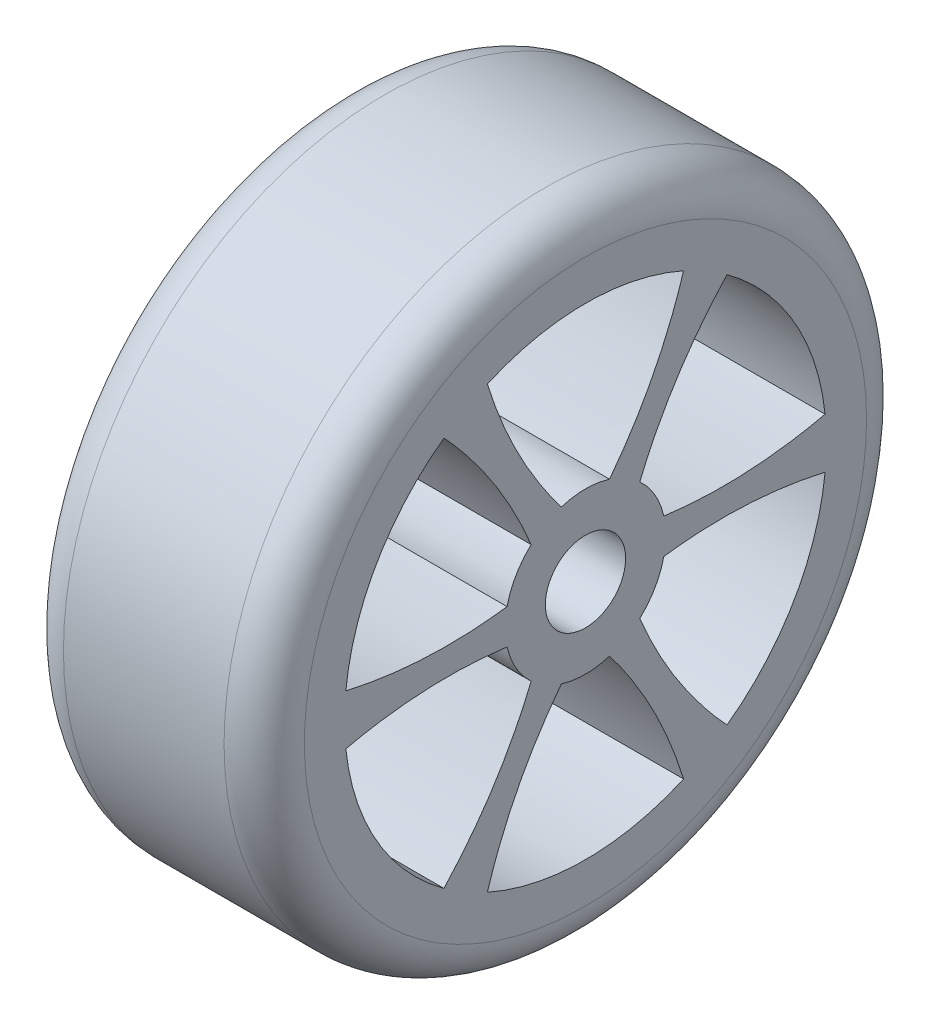
SolidWorks part; units mm, degrees
ref_plane "Front Plane" through (0, 0, 0) normal (1, 0, 0) x (0, 1, 0)
ref_plane "Top Plane" through (0, 0, 0) normal (0, 0, 1) x (0, 1, 0)
ref_plane "Right Plane" through (0, 0, 0) normal (0, 1, 0) x (-1, 0, 0)
sketch "Sketch1" plane through (0, 0, 0) normal (1, 0, 0) x (0, 1, 0)
  line L0 (0, 0) -> (0, 125.8279) construction
  circle A0 centre (0, 0) radius 101.6
  circle A1 centre (0, 0) radius 76.2
  circle A2 centre (0, 0) radius 25.4
  circle A3 centre (0, 0) radius 76.2
  circle A4 centre (0, 0) radius 76.2
  circle A5 centre (0, 0) radius 76.2
  spline S0 degree 2 poles (-22.4008, 72.833) (-10.4924, 49.373) (-10.8441, 22.9688) knots 0 0 0 1 1 1
  spline S1 degree 2 poles (22.4008, 72.833) (10.4924, 49.373) (10.8441, 22.9688) knots 0 0 0 1 1 1
  spline S2 degree 2 poles (72.833, 22.4008) (49.373, 10.4924) (22.9688, 10.8441) knots 0 0 0 1 1 1
  spline S3 degree 2 poles (72.833, -22.4008) (49.373, -10.4924) (22.9688, -10.8441) knots 0 0 0 1 1 1
  spline S4 degree 2 poles (22.4008, -72.833) (10.4924, -49.373) (10.8441, -22.9688) knots 0 0 0 1 1 1
  spline S5 degree 2 poles (-22.4008, -72.833) (-10.4924, -49.373) (-10.8441, -22.9688) knots 0 0 0 1 1 1
  spline S6 degree 2 poles (-72.833, -22.4008) (-49.373, -10.4924) (-22.9688, -10.8441) knots 0 0 0 1 1 1
  spline S7 degree 2 poles (-72.833, 22.4008) (-49.373, 10.4924) (-22.9688, 10.8441) knots 0 0 0 1 1 1
  point P36 (0, 0)
  dimension "D1" = 203.2
  dimension "D2" = 152.4
  dimension "D3" = 50.8
  dimension "D4" = 4
extrude "Boss-Extrude1" add sketch "Sketch1" along normal blind 76.2 contours A0
fillet "Fillet1" radius 12.7 2 edges at (0, 0, -101.6) (76.2, 0, -101.6)
sketch "Sketch2" plane through (76.2, 0, 0) normal (1, 0, 0) x (0, 1, 0)
  line L0 (0, 0) -> (0, 25.4) construction
  line L1 (0, 76.2) -> (0, 107.8241) construction
  arc A0 (-24.2324, 7.6125) -> (-24.2324, -7.6125) centre (0, 0) ccw
  arc A1 (-69.5977, 31.0259) -> (-69.5977, -31.0259) centre (0, 0) ccw
  arc A2 (18.7088, 17.1797) -> (5.5236, 24.7921) centre (0, 0) ccw
  arc A3 (61.668, 44.7604) -> (7.9296, 75.7863) centre (0, 0) ccw
  arc A4 (24.2324, -7.6125) -> (24.2324, 7.6125) centre (0, 0) ccw
  arc A5 (69.5977, -31.0259) -> (69.5977, 31.0259) centre (0, 0) ccw
  arc A6 (-61.668, -44.7604) -> (-7.9296, -75.7863) centre (0, 0) ccw
  arc A7 (-18.7088, -17.1797) -> (-5.5236, -24.7921) centre (0, 0) ccw
  arc A8 (5.5236, -24.7921) -> (18.7088, -17.1797) centre (0, 0) ccw
  arc A9 (7.9296, -75.7863) -> (61.668, -44.7604) centre (0, 0) ccw
  arc A10 (-7.9296, 75.7863) -> (-61.668, 44.7604) centre (0, 0) ccw
  arc A11 (-5.5236, 24.7921) -> (-18.7088, 17.1797) centre (0, 0) ccw
  spline S0 degree 2 poles (-5.5236, 24.7921) (-2.1408, 50.4497) (-7.9296, 75.7863) knots 0 0 0 1 1 1
  spline S1 degree 2 poles (5.5236, 24.7921) (2.1408, 50.4497) (7.9296, 75.7863) knots 0 0 0 1 1 1
  spline S2 degree 2 poles (18.7088, 17.1797) (42.6203, 27.0789) (61.668, 44.7604) knots 0 0 0 1 1 1
  spline S3 degree 2 poles (24.2324, 7.6125) (44.7612, 23.3709) (69.5977, 31.0259) knots 0 0 0 1 1 1
  spline S4 degree 2 poles (24.2324, -7.6125) (44.7612, -23.3709) (69.5977, -31.0259) knots 0 0 0 1 1 1
  spline S5 degree 2 poles (18.7088, -17.1797) (42.6203, -27.0789) (61.668, -44.7604) knots 0 0 0 1 1 1
  spline S6 degree 2 poles (5.5236, -24.7921) (2.1408, -50.4497) (7.9296, -75.7863) knots 0 0 0 1 1 1
  spline S7 degree 2 poles (-5.5236, -24.7921) (-2.1408, -50.4497) (-7.9296, -75.7863) knots 0 0 0 1 1 1
  spline S8 degree 2 poles (-18.7088, -17.1797) (-42.6203, -27.0789) (-61.668, -44.7604) knots 0 0 0 1 1 1
  spline S9 degree 2 poles (-24.2324, -7.6125) (-44.7612, -23.3709) (-69.5977, -31.0259) knots 0 0 0 1 1 1
  spline S10 degree 2 poles (-24.2324, 7.6125) (-44.7612, 23.3709) (-69.5977, 31.0259) knots 0 0 0 1 1 1
  spline S11 degree 2 poles (-18.7088, 17.1797) (-42.6203, 27.0789) (-61.668, 44.7604) knots 0 0 0 1 1 1
  point P44 (0, 0)
  dimension "D1" = 50.8
  dimension "D2" = 152.4
extrude "Cut-Extrude1" cut sketch "Sketch2" against normal through all both and the other way through all
sketch "Sketch5" plane through (76.2, 0, 0) normal (1, 0, 0) x (0, 1, 0)
  circle A0 centre (0, 0) radius 12.7
  dimension "D1" = 25.4
extrude "Cut-Extrude2" cut sketch "Sketch5" against normal through all both and the other way through all
